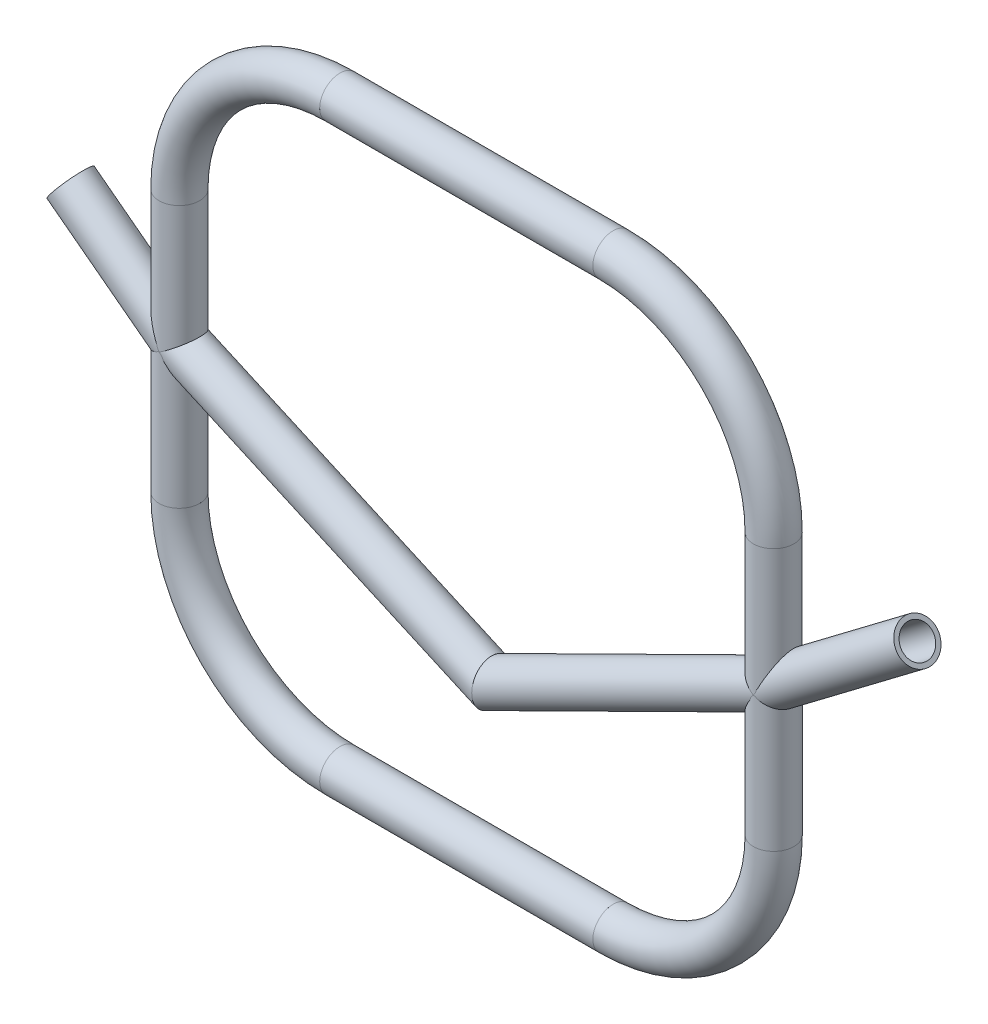
SolidWorks part; units mm, degrees
ref_plane "Front Plane" through (0, 0, 0) normal (0, 0, 1) x (1, 0, 0)
ref_plane "Top Plane" through (0, 0, 0) normal (0, 1, 0) x (1, 0, 0)
ref_plane "Right Plane" through (0, 0, 0) normal (1, 0, 0) x (0, 0, -1)
sketch "Sketch1" plane through (0, 0, 0) normal (0, 0, 1) x (1, 0, 0)
  line L0 (0, 0) -> (0, 45.7431) construction
  line L1 (-21.4218, 45.7431) -> (21.4218, 45.7431)
  line L2 (-46.6062, 20.5587) -> (-46.6062, -20.5587)
  line L3 (-21.4218, -45.7431) -> (21.4218, -45.7431)
  line L4 (46.6062, 20.5587) -> (46.6062, -20.5587)
  line L5 (-39.1608, 38.4356) -> (39.1608, -38.4356) construction
  line L6 (-39.1608, -38.4356) -> (39.1608, 38.4356) construction
  line L7 (0, 0) -> (46.6062, 0) construction
  line L8 (69.1504, 17.0324) -> (46.6062, 0)
  line L9 (46.6062, 0) -> (2.4241, -21.8806)
  line L10 (2.4241, -21.8806) -> (-46.6062, 0)
  line L11 (-46.6062, 0) -> (-63.6643, 12.9497)
  arc A0 (-46.6062, 20.5587) -> (-21.4218, 45.7431) centre (-21.4218, 20.5587) cw
  arc A1 (46.6062, 20.5587) -> (21.4218, 45.7431) centre (21.4218, 20.5587) ccw
  arc A2 (46.6062, -20.5587) -> (21.4218, -45.7431) centre (21.4218, -20.5587) cw
  arc A3 (-46.6062, -20.5587) -> (-21.4218, -45.7431) centre (-21.4218, -20.5587) ccw
  point P0 (0, 0)
  dimension "D3" = 25.1844
other "Weld tubing 0.250 X 0.028(1)"
ref_plane "Plane1" through (-46.6062, 20.5587, 0) normal (0, -1, 0) x (1, 0, 0)
sketch "Sketch17" plane through (-46.6062, 20.5587, 0) normal (0, -1, 0) x (1, 0, 0)
  circle A0 centre (0, 0) radius 3.175
  circle A1 centre (0, 0) radius 2.4638
  point P5 (0, 0)
  dimension "D1" = 6.35
  dimension "D2" = 0.7112
other "Weld tubing 0.250 X 0.028(2)"
ref_plane "Plane2" through (69.1504, 17.0324, 0) normal (-0.7979, -0.6028, 0) x (0.6028, -0.7979, 0)
sketch "Sketch18" plane through (69.1504, 17.0324, 0) normal (-0.7979, -0.6028, 0) x (0.6028, -0.7979, 0)
  circle A0 centre (0, 0) radius 3.175
  circle A1 centre (0, 0) radius 2.4638
  point P5 (0, 0)
  dimension "D1" = 6.35
  dimension "D2" = 0.7112
other "Trim/Extend2"
other "Trim/Extend3"
